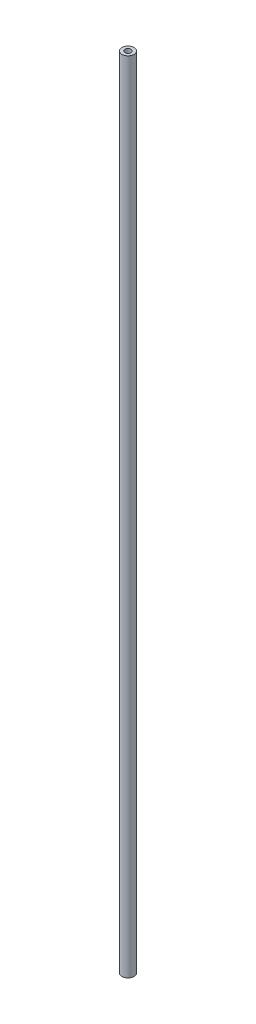
SolidWorks part; units mm, degrees
material "6061-T6 (SS)"
ref_plane "Front Plane" through (0, 0, 0) normal (1, 0, 0) x (0, 1, 0)
ref_plane "Top Plane" through (0, 0, 0) normal (0, 0, 1) x (0, 1, 0)
ref_plane "Right Plane" through (0, 0, 0) normal (0, 1, 0) x (-1, 0, 0)
sketch "Sketch1" plane through (0, 0, 0) normal (0, 1, 0) x (-1, 0, 0)
  circle A0 centre (0, 0) radius 6.35
  circle A1 centre (0, 0) radius 3.175
  dimension "D1" = 12.7
  dimension "D2" = 6.35
extrude "Boss-Extrude1" add sketch "Sketch1" along normal blind 841.6032
equation "\"F\"= 400'Tencile Force Applied (lbf)"
equation "\"E\"= 10 ^ 7'Youngs Modulus Al (PSI)"
equation "\"defl\"= 0.009in'Max Deflection (Inch)"
equation "\"do\" = 0.5'Outer Diameter (inch)"
equation "\"di\" = 0.25'Inner Diameter (inch)"
equation "\"A\"= ( pi / 4 ) * ( \"do\" ^ 2 - \"di\" ^ 2 )'Cross Secgtional Area (inch^2)"
equation "\"L\"= ( \"defl\" * \"A\" * \"E\" ) / \"F\"'Designed Length (inch)"
equation "\"D1@Boss-Extrude1\"=\"L\""
equation "\"D1@Sketch1\"=\"do\""
equation "\"D2@Sketch1\"=\"di\""
